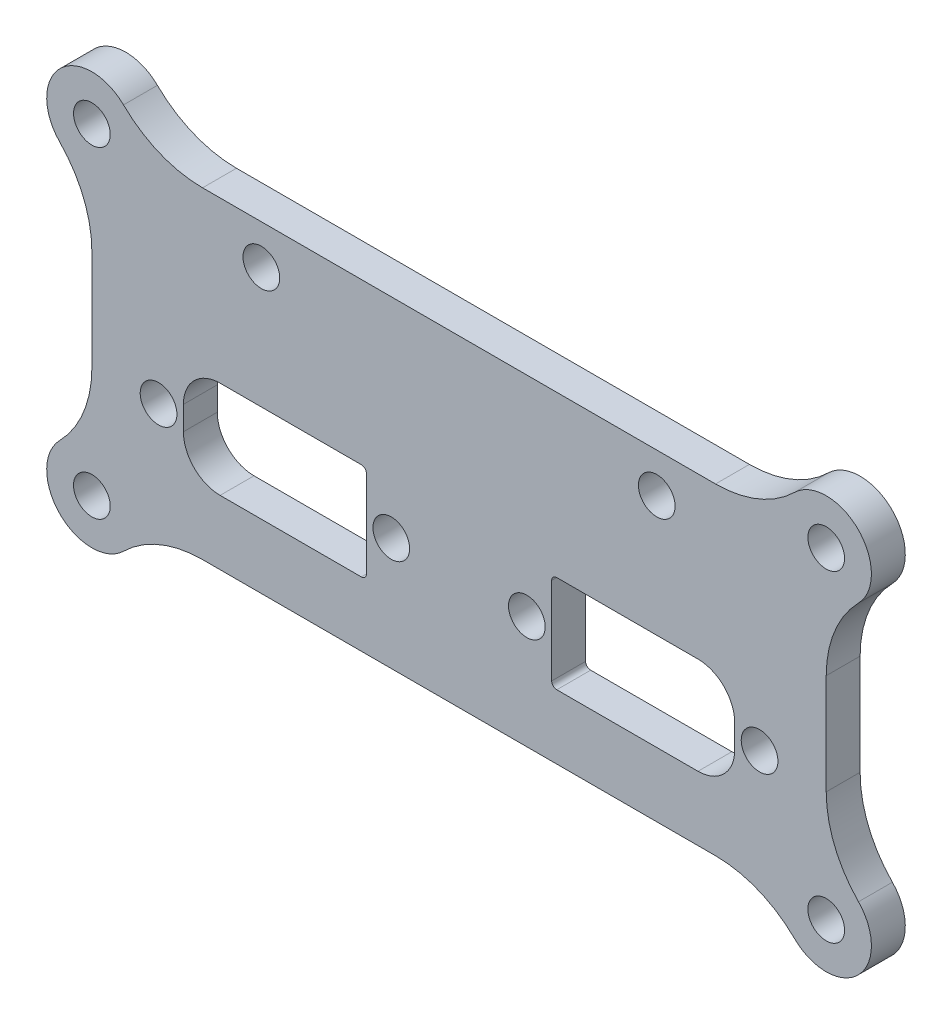
SolidWorks part; units mm, degrees
material "ABS"
ref_plane "Спереди" through (0, 0, 0) normal (0, 0, 1) x (1, 0, 0)
ref_plane "Сверху" through (0, 0, 0) normal (0, 1, 0) x (1, 0, 0)
ref_plane "Справа" through (0, 0, 0) normal (1, 0, 0) x (0, 0, -1)
sketch "Эскиз1" plane through (0, 0, 0) normal (0, 0, 1) x (1, 0, 0)
  line L0 (-32.5, 0) -> (32.5, 0)
  line L3 (-32.5, 28.5) -> (32.5, 28.5)
  line L4 (32.5, 0) -> (32.5, 28.5)
  line L6 (-32.5, 28.5) -> (0, 0) construction
  line L7 (-32.5, 0) -> (-32.5, 28.5)
  line L8 (0, 0) -> (32.5, 28.5) construction
  circle A0 centre (-32.5, 28.5) radius 1.625
  arc A1 (-28.5, 28.5) -> (-32.5, 24.5) centre (-32.5, 28.5) ccw
  circle A2 centre (32.5, 28.5) radius 1.625
  arc A3 (32.5, 24.5) -> (28.5, 28.5) centre (32.5, 28.5) ccw
  arc A8 (-30.2165, -39.7842) -> (-30.0697, -39.6771) centre (-32.5, -36.5) ccw [skipped]
  arc A9 (-30.8963, -36.7625) -> (-30.8944, -36.7501) centre (-32.5, -36.5) ccw [skipped]
  arc A10 (34.8906, -39.707) -> (34.7835, -39.7842) centre (32.5, -36.5) ccw [skipped]
  arc A11 (34.1056, -36.7501) -> (34.1094, -36.7244) centre (32.5, -36.5) ccw [skipped]
  circle A12 centre (-32.5, 0) radius 1.625
  arc A13 (-32.5, 4) -> (-28.5, 0) centre (-32.5, 0) ccw
  arc A14 (28.5, 0) -> (32.5, 4) centre (32.5, 0) ccw
  circle A15 centre (32.5, 0) radius 1.625
  point P0 (0, 0)
  point P20 (0, -4)
  dimension "D2" = 3.25
  dimension "D3" = 8
  dimension "D8" = 3.25
  dimension "D9" = 8
  dimension "D10" = 3.25
  dimension "D11" = 8
  dimension "D1" = 28.5
  dimension "D5" = 65
  dimension "D6" = 32.5
  dimension "D7" = 90
  dimension "D4" = 4
extrude "Бобышка-Вытянуть1" add sketch "Эскиз1" along normal blind 3
fillet "Скругление1" radius 10 8 edges at (-28.5, 28.5, 1.5) (28.5, 28.5, 1.5) (32.5, 24.5, 1.5) (-32.5, 24.5, 1.5) (32.5, 4, 1.5) (28.5, 0, 1.5) (-28.5, 0, 1.5) (-32.5, 4, 1.5)
sketch "Эскиз3" plane through (0, 0, 0) normal (0, 0, -1) x (-1, 0, 0)
  line L0 (0, 28.5) -> (0, -32.5) construction
  line L1 (22.702, 28.5) -> (-22.702, 28.5) construction
  line L3 (-31.8936, 25) -> (26.7306, 25) construction
  circle A0 centre (-17.5, 25) radius 1.625
  circle A1 centre (17.5, 25) radius 1.625
  dimension "D1" = 3.25
  dimension "D2" = 17.5
  dimension "D3" = 25
extrude "Вырез-Вытянуть1" cut sketch "Эскиз3" against normal blind 10
sketch "Эскиз4" plane through (0, 0, 3) normal (0, 0, 1) x (1, 0, 0)
  line L0 (0, 28.5) -> (0, 0) construction
  line L1 (8.65, 14.3) -> (21.15, 14.3)
  line L2 (24.4, 11.05) -> (24.4, 8.95)
  line L3 (21.15, 5.7) -> (8.65, 5.7)
  line L4 (-8.65, 14.05) -> (-21.15, 14.05)
  line L5 (-8.45, 6.15) -> (-8.45, 13.85)
  line L6 (-21.15, 5.95) -> (-8.65, 5.95)
  line L7 (-24.15, 11.05) -> (-24.15, 8.95)
  line L8 (-8.65, 14.05) -> (-21.15, 14.05)
  line L9 (-8.45, 6.15) -> (-8.45, 13.85)
  line L10 (-21.15, 5.95) -> (-8.65, 5.95)
  line L11 (-24.15, 11.05) -> (-24.15, 8.95)
  line L12 (-8.2, 6.15) -> (-8.2, 13.85)
  line L13 (-21.15, 5.7) -> (-8.65, 5.7)
  line L14 (-24.4, 11.05) -> (-24.4, 8.95)
  line L15 (-8.65, 14.3) -> (-21.15, 14.3)
  line L16 (-8.2, 6.15) -> (-8.2, 13.85)
  line L17 (-21.15, 5.7) -> (-8.65, 5.7)
  line L18 (-24.4, 11.05) -> (-24.4, 8.95)
  line L19 (-8.65, 14.3) -> (-21.15, 14.3)
  line L20 (-22.702, 0) -> (22.702, 0)
  line L21 (32.5, 9.798) -> (32.5, 18.702)
  line L22 (22.702, 28.5) -> (-22.702, 28.5)
  line L23 (-32.5, 18.702) -> (-32.5, 9.798)
  line L24 (-22.702, 0) -> (22.702, 0)
  line L25 (32.5, 9.798) -> (32.5, 18.702)
  line L26 (22.702, 28.5) -> (-22.702, 28.5)
  line L27 (-32.5, 18.702) -> (-32.5, 9.798)
  line L28 (8.2, 6.15) -> (8.2, 13.85)
  line L29 (24.15, 11.05) -> (24.15, 8.95)
  line L30 (21.15, 5.95) -> (8.65, 5.95)
  line L31 (8.45, 6.15) -> (8.45, 13.85)
  line L32 (8.65, 14.05) -> (21.15, 14.05)
  arc A0 (8.2, 13.85) -> (8.65, 14.3) centre (8.65, 13.85) cw
  arc A1 (21.15, 14.3) -> (24.4, 11.05) centre (21.15, 11.05) cw
  arc A2 (24.4, 8.95) -> (21.15, 5.7) centre (21.15, 8.95) cw
  arc A3 (8.65, 5.7) -> (8.2, 6.15) centre (8.65, 6.15) cw
  arc A4 (-8.45, 13.85) -> (-8.65, 14.05) centre (-8.65, 13.85) ccw
  arc A5 (-8.65, 5.95) -> (-8.45, 6.15) centre (-8.65, 6.15) ccw
  arc A6 (-24.15, 8.95) -> (-21.15, 5.95) centre (-21.15, 8.95) ccw
  arc A7 (-21.15, 14.05) -> (-24.15, 11.05) centre (-21.15, 11.05) ccw
  arc A8 (-8.45, 13.85) -> (-8.65, 14.05) centre (-8.65, 13.85) ccw
  arc A9 (-8.65, 5.95) -> (-8.45, 6.15) centre (-8.65, 6.15) ccw
  arc A10 (-24.15, 8.95) -> (-21.15, 5.95) centre (-21.15, 8.95) ccw
  arc A11 (-21.15, 14.05) -> (-24.15, 11.05) centre (-21.15, 11.05) ccw
  arc A12 (-8.65, 5.7) -> (-8.2, 6.15) centre (-8.65, 6.15) ccw
  arc A13 (-24.4, 8.95) -> (-21.15, 5.7) centre (-21.15, 8.95) ccw
  arc A14 (-21.15, 14.3) -> (-24.4, 11.05) centre (-21.15, 11.05) ccw
  arc A15 (-8.2, 13.85) -> (-8.65, 14.3) centre (-8.65, 13.85) ccw
  arc A16 (-8.65, 5.7) -> (-8.2, 6.15) centre (-8.65, 6.15) ccw
  arc A17 (-24.4, 8.95) -> (-21.15, 5.7) centre (-21.15, 8.95) ccw
  arc A18 (-21.15, 14.3) -> (-24.4, 11.05) centre (-21.15, 11.05) ccw
  arc A19 (-8.2, 13.85) -> (-8.65, 14.3) centre (-8.65, 13.85) ccw
  arc A20 (21.15, 14.05) -> (24.15, 11.05) centre (21.15, 11.05) cw
  arc A21 (24.15, 8.95) -> (21.15, 5.95) centre (21.15, 8.95) cw
  arc A22 (8.65, 5.95) -> (8.45, 6.15) centre (8.65, 6.15) cw
  arc A23 (8.45, 13.85) -> (8.65, 14.05) centre (8.65, 13.85) cw
  arc A28 (29.7006, -2.8571) -> (22.702, 0) centre (22.702, -10) ccw
  arc A29 (29.7006, -2.8571) -> (35.3571, 2.7994) centre (32.5, 0) ccw
  arc A30 (32.5, 9.798) -> (35.3571, 2.7994) centre (42.5, 9.798) ccw
  arc A31 (35.3571, 25.7006) -> (32.5, 18.702) centre (42.5, 18.702) ccw
  arc A32 (35.3571, 25.7006) -> (29.7006, 31.3571) centre (32.5, 28.5) ccw
  arc A33 (22.702, 28.5) -> (29.7006, 31.3571) centre (22.702, 38.5) ccw
  arc A34 (-29.7006, 31.3571) -> (-22.702, 28.5) centre (-22.702, 38.5) ccw
  arc A35 (-29.7006, 31.3571) -> (-35.3571, 25.7006) centre (-32.5, 28.5) ccw
  arc A36 (-32.5, 18.702) -> (-35.3571, 25.7006) centre (-42.5, 18.702) ccw
  arc A37 (-35.3571, 2.7994) -> (-32.5, 9.798) centre (-42.5, 9.798) ccw
  arc A38 (-35.3571, 2.7994) -> (-29.7006, -2.8571) centre (-32.5, 0) ccw
  arc A39 (-22.702, 0) -> (-29.7006, -2.8571) centre (-22.702, -10) ccw
  arc A40 (29.7006, -2.8571) -> (22.702, 0) centre (22.702, -10) ccw
  arc A41 (29.7006, -2.8571) -> (35.3571, 2.7994) centre (32.5, 0) ccw
  arc A42 (32.5, 9.798) -> (35.3571, 2.7994) centre (42.5, 9.798) ccw
  arc A43 (35.3571, 25.7006) -> (32.5, 18.702) centre (42.5, 18.702) ccw
  arc A44 (35.3571, 25.7006) -> (29.7006, 31.3571) centre (32.5, 28.5) ccw
  arc A45 (22.702, 28.5) -> (29.7006, 31.3571) centre (22.702, 38.5) ccw
  arc A46 (-29.7006, 31.3571) -> (-22.702, 28.5) centre (-22.702, 38.5) ccw
  arc A47 (-29.7006, 31.3571) -> (-35.3571, 25.7006) centre (-32.5, 28.5) ccw
  arc A48 (-32.5, 18.702) -> (-35.3571, 25.7006) centre (-42.5, 18.702) ccw
  arc A49 (-35.3571, 2.7994) -> (-32.5, 9.798) centre (-42.5, 9.798) ccw
  arc A50 (-35.3571, 2.7994) -> (-29.7006, -2.8571) centre (-32.5, 0) ccw
  arc A51 (-22.702, 0) -> (-29.7006, -2.8571) centre (-22.702, -10) ccw
  dimension "D1" = 0
  dimension "D2" = 0
  dimension "D3" = 0
extrude "Вырез-Вытянуть2" cut sketch "Эскиз4" against normal blind 10 contours L16 A19 L19 A18 L18 A17 L17 A16 A11 L8 A8 L9 A9 L10 A10 L11 | A3 L3 A2 L2 A1 L1 A0 L28 L31 A23 L32 A20 L29 A21 L30 A22
sketch "Эскиз5" plane through (0, 0, 0) normal (0, 0, -1) x (-1, 0, 0)
  circle A1 centre (26.6, 10) radius 1.625
  circle A2 centre (26.6, 10) radius 1.625
  circle A3 centre (-26.6, 10) radius 1.625
  circle A4 centre (-26.6, 10) radius 1.625
  circle A5 centre (-6, 10) radius 1.625
  circle A6 centre (-6, 10) radius 1.625
  circle A7 centre (6, 10) radius 1.625
  circle A8 centre (6, 10) radius 1.625
  dimension "D1" = 0
  dimension "D2" = 0
  dimension "D3" = 0
  dimension "D4" = 0
extrude "Вырез-Вытянуть3" cut sketch "Эскиз5" against normal blind 10
